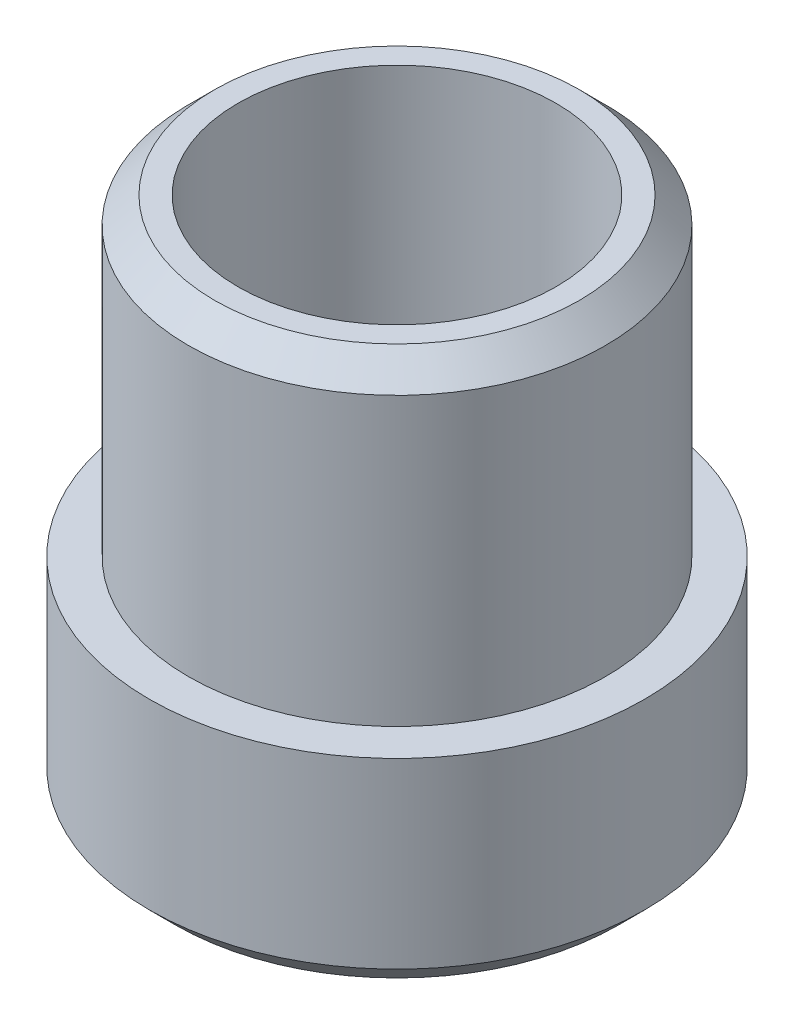
SolidWorks part; units mm, degrees
ref_plane "Front Plane" through (0, 0, 0) normal (0, 0, 1) x (1, 0, 0)
ref_plane "Top Plane" through (0, 0, 0) normal (0, 1, 0) x (1, 0, 0)
ref_plane "Right Plane" through (0, 0, 0) normal (1, 0, 0) x (0, 0, -1)
sketch "Sketch1" plane through (0, 0, 0) normal (0, 1, 0) x (1, 0, 0)
  circle A0 centre (0, 0) radius 4.75
  dimension "D1" = 9.5
extrude "Boss-Extrude1" add sketch "Sketch1" along normal blind 4
sketch "Sketch2" plane through (0, 4, 0) normal (0, 1, 0) x (1, 0, 0)
  circle A0 centre (0, 0) radius 4
  circle A1 centre (0, 0) radius 3.05
  dimension "D1" = 6.1
  dimension "D2" = 8
extrude "Boss-Extrude2" add sketch "Sketch2" along normal blind 6
chamfer "Chamfer1" distance 0.5 angle 45 2 edges at (0, 0, 4.75) (0, 10, 4)
